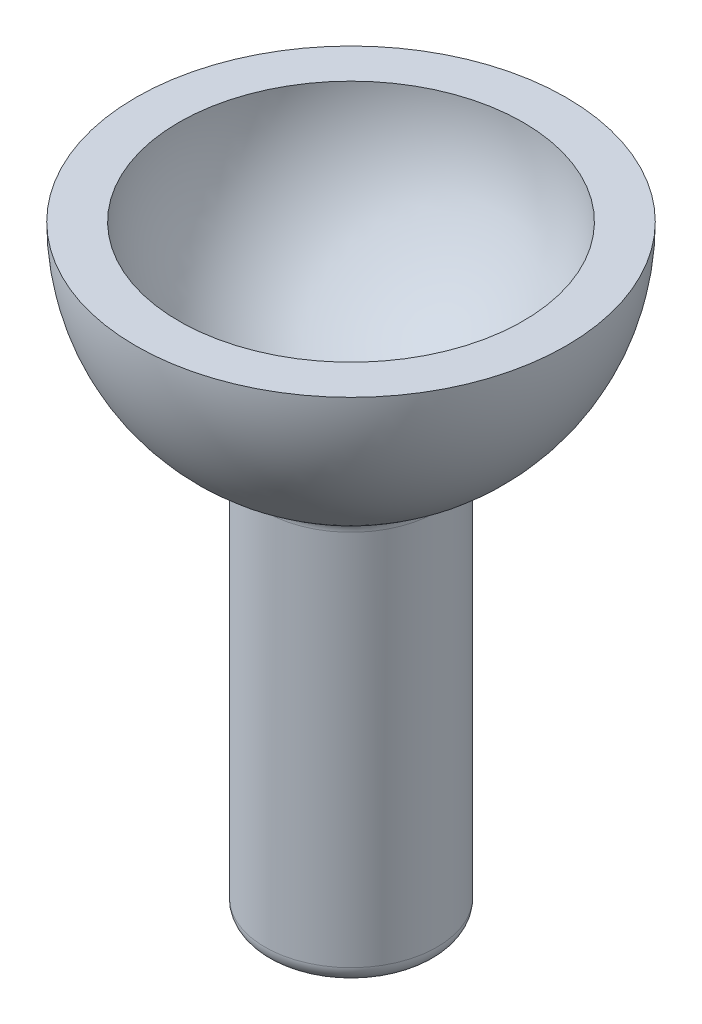
SolidWorks part; units mm, degrees
ref_plane "Front Plane" through (0, 0, 0) normal (0, 0, 1) x (1, 0, 0)
ref_plane "Top Plane" through (0, 0, 0) normal (0, 1, 0) x (1, 0, 0)
ref_plane "Right Plane" through (0, 0, 0) normal (1, 0, 0) x (0, 0, -1)
sketch "Sketch1" plane through (0, 0, 0) normal (0, 0, 1) x (1, 0, 0)
  line L0 (0, -11.8769) -> (0, 7.935) construction
  line L1 (0, 6) -> (0, 5)
  line L3 (0, 0) -> (17.3612, 0) construction
  line L9 (10, 0) -> (12.5, 0)
  line L13 (0, -10) -> (0, -35)
  line L16 (0, -35) -> (5, -35)
  line L17 (5, -11.4564) -> (5, -35)
  arc A1 (0, -10) -> (10, 0) centre (0, 0) ccw
  arc A3 (12.5, 0) -> (5, -11.4564) centre (0, 0) cw
  point P7 (-0.4637, -9.9892)
  point P8 (4.5363, -11.6478)
  point P16 (0, -11.8769)
  dimension "D1" = 10
  dimension "D2" = 5
  dimension "D3" = 2.5
  dimension "D4" = 25
revolve "Revolve2" add sketch "Sketch1" angle 360 about L0
fillet "Fillet1" radius 1 2 edges at (0, -35, -5) (0, -11.4564, -5)
